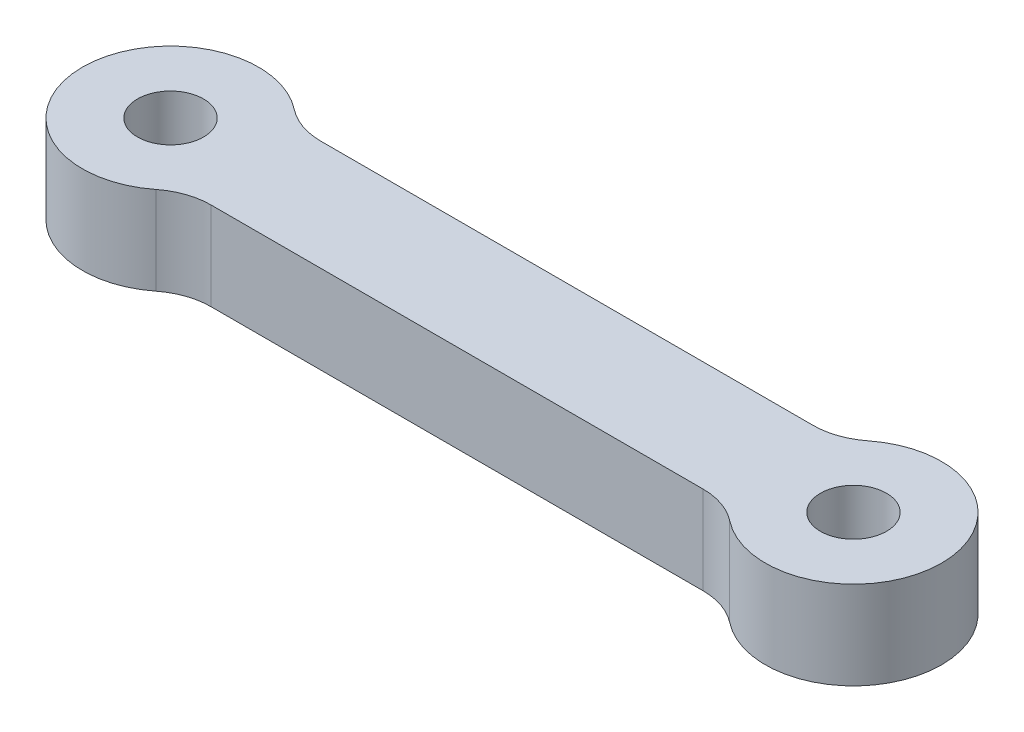
SolidWorks part; units mm, degrees
ref_plane "Front Plane" through (0, 0, 0) normal (0, 0, 1) x (1, 0, 0)
ref_plane "Top Plane" through (0, 0, 0) normal (0, 1, 0) x (1, 0, 0)
ref_plane "Right Plane" through (0, 0, 0) normal (1, 0, 0) x (0, 0, -1)
sketch "Sketch1" plane through (0, 0, 0) normal (0, 1, 0) x (1, 0, 0)
  line L0 (-15.5, 0) -> (15.5, 0) construction
  line L1 (0, 0) -> (0, 3.5462) construction
  line L3 (11.1699, 2.5) -> (-11.1699, 2.5)
  line L5 (11.1699, -2.5) -> (-11.1699, -2.5)
  line L7 (12.3775, 2.5) -> (-12.3775, -2.5) construction
  line L8 (12.3775, -2.5) -> (-12.3775, 2.5) construction
  arc A0 (-13.0256, 3.1429) -> (-13.0256, -3.1429) centre (-15.5, 0) ccw
  circle A1 centre (-15.5, 0) radius 1.5
  circle A2 centre (15.5, 0) radius 1.5
  arc A3 (13.0256, 3.1429) -> (13.0256, -3.1429) centre (15.5, 0) cw
  arc A4 (13.0256, 3.1429) -> (11.1699, 2.5) centre (11.1699, 5.5) cw
  arc A5 (11.1699, -2.5) -> (13.0256, -3.1429) centre (11.1699, -5.5) cw
  arc A6 (-11.1699, -2.5) -> (-13.0256, -3.1429) centre (-11.1699, -5.5) ccw
  arc A7 (-11.1699, 2.5) -> (-13.0256, 3.1429) centre (-11.1699, 5.5) cw
  dimension "D1" = 8
  dimension "D2" = 3
  dimension "D5" = 3
  dimension "D3" = 5
  dimension "D4" = 31
extrude "Boss-Extrude1" add sketch "Sketch1" along normal blind 4
